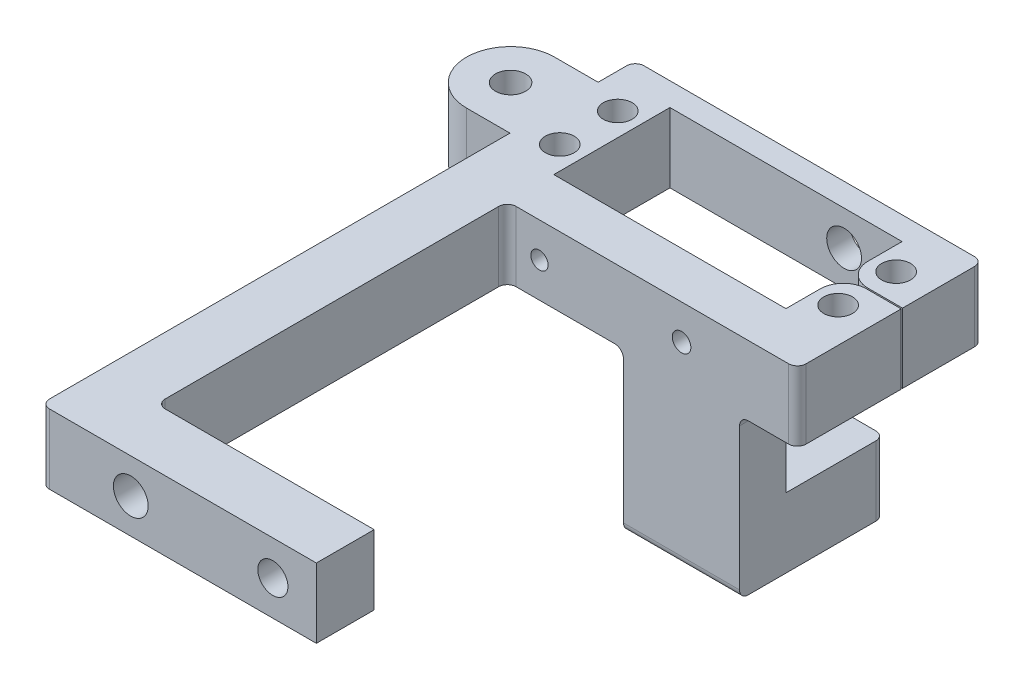
SolidWorks part; units mm, degrees
ref_plane "Front Plane" through (0, 0, 0) normal (0, 0, 1) x (1, 0, 0)
ref_plane "Top Plane" through (0, 0, 0) normal (0, 1, 0) x (1, 0, 0)
ref_plane "Right Plane" through (0, 0, 0) normal (1, 0, 0) x (0, 0, -1)
sketch "Sketch1" plane through (0, 0, 0) normal (0, 1, 0) x (1, 0, 0)
  line L0 (20.015, 0) -> (27.985, 0)
  line L1 (27.985, -14.015) -> (-27.985, -14.015)
  line L2 (27.985, -14.015) -> (27.985, 14.015)
  line L3 (27.985, 14.015) -> (-27.985, 14.015)
  line L4 (-27.985, -14.015) -> (-27.985, 14.015)
  line L5 (27.985, -14.015) -> (-27.985, 14.015) construction
  line L6 (27.985, 14.015) -> (-27.985, -14.015) construction
  line L7 (20.015, -10.015) -> (-20.015, -10.015)
  line L8 (20.015, -10.015) -> (20.015, 10.015)
  line L9 (20.015, 10.015) -> (-20.015, 10.015)
  line L10 (-20.015, -10.015) -> (-20.015, 10.015)
  line L11 (20.015, -10.015) -> (-20.015, 10.015) construction
  line L12 (20.015, 10.015) -> (-20.015, -10.015) construction
  line L13 (24, -5) -> (-24, -5) construction
  line L14 (24, -5) -> (24, 5) construction
  line L15 (24, 5) -> (-24, 5) construction
  line L16 (-24, -5) -> (-24, 5) construction
  line L17 (24, -5) -> (-24, 5) construction
  line L18 (24, 5) -> (-24, -5) construction
  line L19 (-27.985, -14.015) -> (-27.985, -18.015)
  line L20 (-27.985, -18.015) -> (27.985, -18.015)
  line L21 (27.985, -18.015) -> (27.985, -14.015)
  line L22 (27.985, 14.015) -> (29.985, 14.015)
  line L23 (29.985, 14.015) -> (29.985, 0.115)
  line L24 (29.985, 0.115) -> (24, 0.115)
  line L25 (27.985, -14.015) -> (29.985, -14.015)
  line L26 (29.985, -14.015) -> (29.985, -0.115)
  line L27 (29.985, -0.115) -> (24, -0.115)
  line L28 (27.985, -18.015) -> (29.985, -18.015)
  line L29 (29.985, -18.015) -> (29.985, -14.015)
  line L30 (-27.985, 14.015) -> (-29.985, 14.015)
  line L31 (-29.985, 14.015) -> (-29.985, -18.015)
  line L32 (-29.985, -18.015) -> (-27.985, -18.015)
  line L33 (-20.015, -18.015) -> (-20.015, -78.515)
  line L34 (-20.015, -78.515) -> (17.515, -78.515)
  line L35 (17.515, -78.515) -> (17.515, -88.485)
  line L36 (17.515, -88.485) -> (-29.985, -88.485)
  line L37 (-29.985, -88.485) -> (-29.985, -18.015)
  line L38 (-20.015, -78.515) -> (-29.985, -78.515) construction
  line L39 (-37.485, 7.6) -> (-29.985, 7.6)
  line L40 (-37.485, -7.6) -> (-29.985, -7.6)
  line L41 (-37.485, 0) -> (-29.985, 0) construction
  circle A1 centre (24, 5) radius 2.485
  circle A2 centre (24, -5) radius 2.485
  circle A3 centre (-24, -5) radius 2.485
  circle A4 centre (-24, 5) radius 2.485
  arc A5 (20.015, 4.1) -> (27.985, 4.1) centre (24, 4.1) ccw
  arc A6 (20.015, -4.1) -> (27.985, -4.1) centre (24, -4.1) cw
  circle A7 centre (-37.485, 0) radius 2.6
  arc A8 (-37.485, 7.6) -> (-37.485, -7.6) centre (-37.485, 0) ccw
  point P0 (0, 0)
  point P6 (0, 0)
  point P11 (0, 0)
  point P47 (-38.0516, 0)
  dimension "D1" = 4.97
  dimension "D7" = 4.1
  dimension "D8" = 4.1
  dimension "D14" = 5.2
  dimension "D15" = 5
  dimension "D16" = 7.5
  dimension "D2" = 48
  dimension "D3" = 4
  dimension "D4" = 40.03
  dimension "D5" = 20.03
  dimension "D6" = 10
  dimension "D9" = 4
  dimension "D10" = 2
  dimension "D11" = 2
  dimension "D12" = 60.5
  dimension "D13" = 47.5
extrude "Boss-Extrude1" add sketch "Sketch1" along normal mid plane 12 contours A6 L8 L7 L10 L9 A5 L2 L3 L4 L1 A4 A3 A2 A1 | L20 L21 L1 L19 | L24 L23 L22 L2 | L26 L27 L2 L25 | L27 A6 L2 | A5 L24 L2 | L28 L29 L25 L21 | L31 L32 L19 L4 L30 | L37 L36 L35 L34 L33 L20 L32 | L39 A8 L40 L37 L31 A7
sketch "Sketch2" plane through (0, -6, 0) normal (0, -1, 0) x (1, 0, 0)
  circle A0 centre (24, -5) radius 2.485 construction
  circle A1 centre (24, 5) radius 2.485 construction
  circle A2 centre (-24, -5) radius 2.485 construction
  circle A3 centre (-24, 5) radius 2.485 construction
  circle A4 centre (24, -5) radius 2.485
  circle A5 centre (24, 5) radius 2.485
  circle A6 centre (-24, -5) radius 2.485
  circle A7 centre (-24, 5) radius 2.485
extrude "Boss-Extrude2" add sketch "Sketch2" against normal offset from surface (2 mm away) 10 up to face at (-0.0541, 6, 15.5455)
sketch "Sketch3" plane through (0, 0, 18.015) normal (0, 0, 1) x (1, 0, 0)
  line L0 (10.015, 0) -> (-10.485, 0) construction
  line L1 (-10.485, 0) -> (-14.485, 0) construction
  circle A2 centre (10.015, 0) radius 1.6
  circle A3 centre (-14.485, 0) radius 1.6
  dimension "D3" = 3.2
  dimension "D4" = 3.2
  dimension "D1" = 4
  dimension "D2" = 20.5
  dimension "D5" = 10
extrude "Cut-Extrude1" cut sketch "Sketch3" against normal blind 10 contours A2
sketch "Sketch4" plane through (0, 0, -14.015) normal (0, 0, -1) x (-1, 0, 0)
  line L4 (-29.985, -6) -> (29.985, -6)
  line L5 (29.985, -6) -> (29.985, 6)
  line L6 (29.985, 6) -> (-29.985, 6)
  line L7 (-29.985, 6) -> (-29.985, -6)
  line L8 (-29.985, -6) -> (29.985, -6)
  line L10 (29.985, 6) -> (-29.985, 6)
  line L12 (-29.985, 6) -> (-29.985, -6)
  line L13 (29.985, -6) -> (29.985, 6)
  circle A2 centre (-10.015, 0) radius 3
  circle A6 centre (-10.015, 0) radius 1.6 construction
  circle A7 centre (-10.015, 0) radius 1.6 construction
  dimension "D2" = 6
  dimension "D1" = 0
extrude "Cut-Extrude2" cut sketch "Sketch4" against normal offset from surface (28.03 mm away) 4 contours A2 up to face at (11.615, 0, 10.015) offset beyond the face yes
sketch "Sketch5" plane through (0, 0, 0) normal (1, 0, 0) x (0, 0, -1)
  line L0 (-18.015, -6) -> (-10.015, -6)
  line L1 (-10.015, -6) -> (-10.015, -21.5)
  line L2 (-10.015, -21.5) -> (6.985, -21.5)
  line L3 (6.985, -21.5) -> (6.985, -33.5)
  line L4 (6.985, -33.5) -> (-18.015, -33.5)
  line L5 (-18.015, -33.5) -> (-18.015, -6)
  line L6 (-7.6, 6) -> (-88.485, 6) construction
  dimension "D1" = 27.5
  dimension "D2" = 12
  dimension "D3" = 25
extrude "Boss-Extrude3" add sketch "Sketch5" along normal up to surface (20.015 mm away) up to face at (20.015, 0, 7.0575)
sketch "Sketch6" plane through (0, -33.5, 0) normal (0, -1, 0) x (1, 0, 0)
  line L0 (0, 0) -> (10.015, 0) construction
  line L1 (20.015, -4.1) -> (20.015, -10.015) construction
  circle A0 centre (10.015, 0) radius 2.485
  dimension "D2" = 4.97
  dimension "D1" = 10
extrude "Cut-Extrude3" cut sketch "Sketch6" against normal blind 10
sketch "Sketch10" plane through (0, 0, 18.015) normal (0, 0, 1) x (1, 0, 0)
  circle A0 centre (-14.485, 0) radius 1.485
  dimension "D1" = 2.97
extrude "Cut-Extrude6" cut sketch "Sketch10" against normal offset from surface 2 and the other way through all up to face at (13.015, 0, 10.015)
sketch "Sketch9" plane through (0, 0, 78.515) normal (0, 0, -1) x (-1, 0, 0)
  circle A0 centre (-10.015, 0) radius 1.6 construction
  circle A1 centre (-10.015, 0) radius 1.6
  circle A2 centre (14.485, 0) radius 3
  circle A4 centre (-10.015, 0) radius 2.6
  circle M6 centre (14.485, 0) radius 1.485
  dimension "D1" = 5.2
  dimension "D2" = 6
extrude "Cut-Extrude5" cut sketch "Sketch9" against normal through all contours A2 M6 | A1 | A4 A1
fillet "Fillet1" radius 1.5 11 edges at (-20.015, 0, 78.515) (-20.015, 0, 18.015) (20.015, -27.5, -6.985) (0, -27.5, -6.985) (10.0075, -33.5, 18.015) (29.985, 0, 18.015) (29.985, 0, -14.015) (-29.985, 0, 88.485) (-29.985, 0, -14.015) (0, -6, 14.015) (20.015, -6, 14.015)
